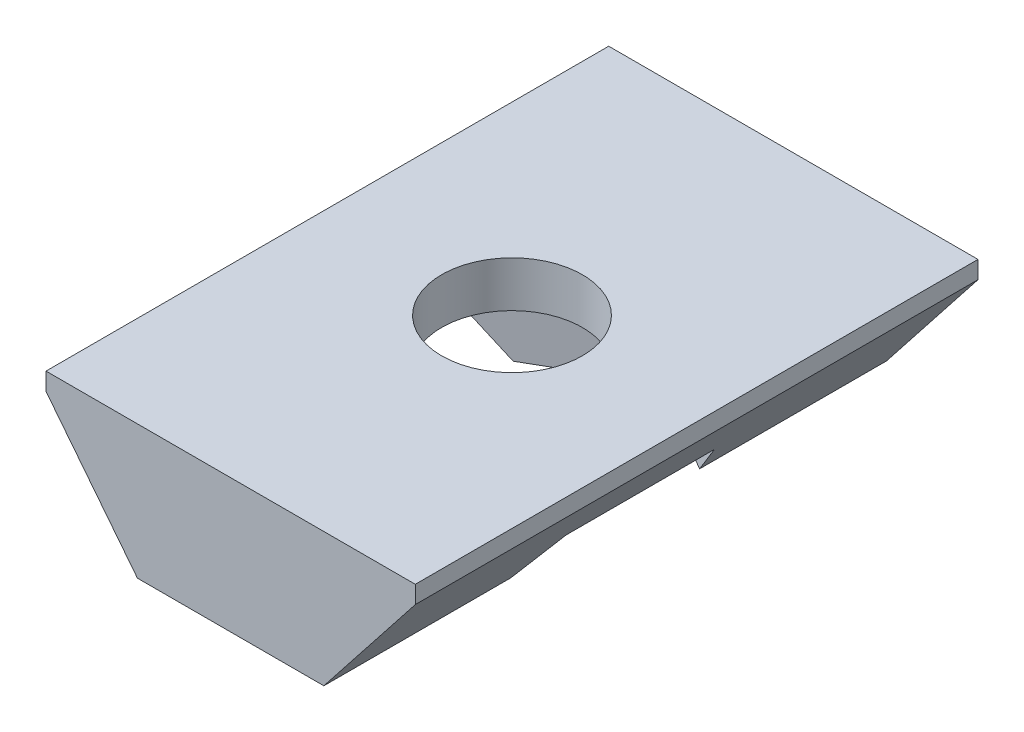
SolidWorks part; units mm, degrees
ref_plane "Plano frontal" through (0, 0, 0) normal (0, 0, 1) x (1, 0, 0)
ref_plane "Plano superior" through (0, 0, 0) normal (0, 1, 0) x (1, 0, 0)
ref_plane "Plano direito" through (0, 0, 0) normal (1, 0, 0) x (0, 0, -1)
sketch "Esboço1" plane through (0, 0, 0) normal (0, 0, 1) x (1, 0, 0)
  line L0 (-2.65, 0) -> (2.65, 0)
  line L1 (-2.65, 0) -> (-5.25, 3.3)
  line L2 (-5.25, 3.8) -> (5.25, 3.8)
  line L3 (5.25, 3.3) -> (2.65, 0)
  line L4 (0, 0) -> (0, 3.8) construction
  line L5 (5.25, 3.3) -> (5.25, 3.8)
  line L6 (-5.25, 3.3) -> (-5.25, 3.8)
  point P3 (0, 0)
  dimension "D1" = 5.3
  dimension "D2" = 10.5
  dimension "D3" = 3.8
  dimension "D4" = 0.5
extrude "Ressalto-extrusão1" add sketch "Esboço1" along normal blind 16
sketch "Esboço2" plane through (0, 3.8, 0) normal (0, 1, 0) x (1, 0, 0)
  line L0 (0, 0) -> (0, -16) construction
  line L1 (5.25, 0) -> (-5.25, 0) construction
  line L2 (5.25, -16) -> (-5.25, -16) construction
  circle A0 centre (0, -8) radius 2
  dimension "D1" = 4
extrude "Corte-extrusão1" cut sketch "Esboço2" against normal through all both and the other way through all
sketch "Esboço3" plane through (0, 0, 0) normal (0, -1, 0) x (1, 0, 0)
  line L1 (0, 12.2147) -> (-3.65, 10.1073)
  line L2 (-3.65, 10.1073) -> (-3.65, 5.8927)
  line L3 (-3.65, 5.8927) -> (0, 3.7853)
  line L4 (0, 3.7853) -> (3.65, 5.8927)
  line L5 (3.65, 5.8927) -> (3.65, 10.1073)
  line L6 (3.65, 10.1073) -> (0, 12.2147)
  circle A0 centre (0, 8) radius 3.65 construction
  dimension "D1" = 7.3
extrude "Corte-extrusão2" cut sketch "Esboço3" against normal blind 2.5
